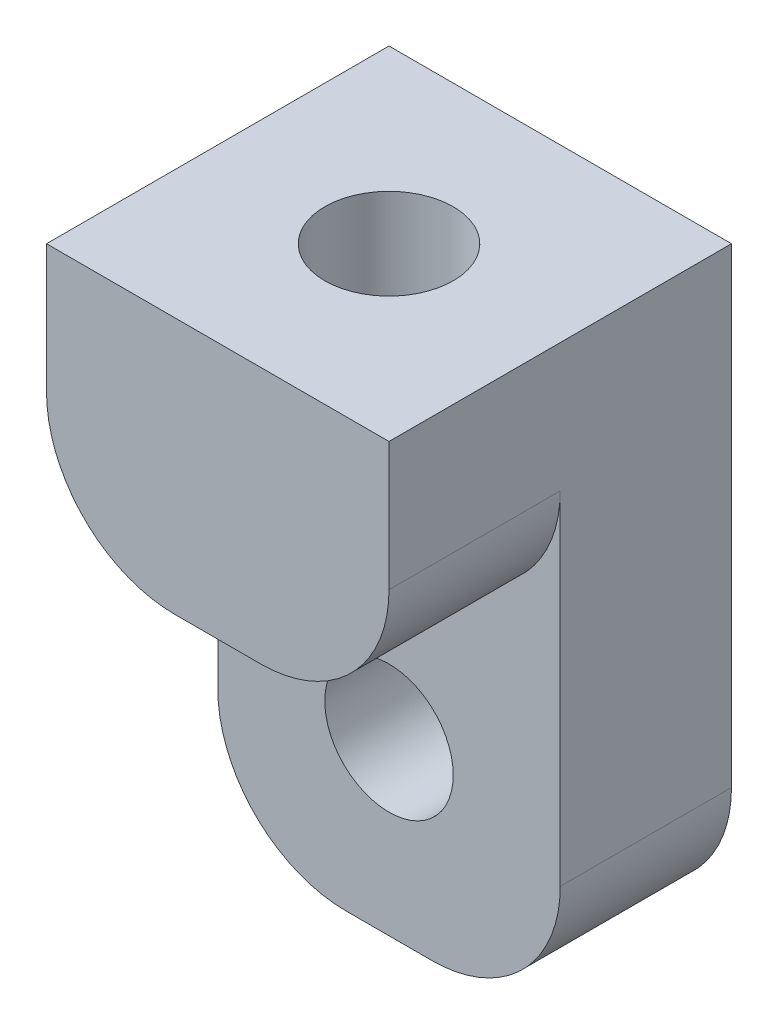
SolidWorks part; units mm, degrees
material "ABS"
ref_plane "Front Plane" through (0, 0, 0) normal (0, 0, 1) x (1, 0, 0)
ref_plane "Top Plane" through (0, 0, 0) normal (0, 1, 0) x (1, 0, 0)
ref_plane "Right Plane" through (0, 0, 0) normal (1, 0, 0) x (0, 0, -1)
sketch "Sketch1" plane through (0, 0, 0) normal (0, 0, 1) x (1, 0, 0)
  line L1 (-20, 50) -> (20, 50)
  line L2 (-20, 50) -> (-20, -20)
  line L3 (-20, -20) -> (20, -20)
  line L4 (20, 50) -> (20, -20)
  circle A0 centre (0, 0) radius 7.5
  point P9 (0, -20)
  dimension "D1" = 15
  dimension "D2" = 20
  dimension "D3" = 70
  dimension "D4" = 40
extrude "Boss-Extrude1" add sketch "Sketch1" along normal blind 40 contours L2 L3 L4 L1
sketch "Sketch2" plane through (0, 50, 0) normal (0, 1, 0) x (1, 0, 0)
  line L0 (-20, 0) -> (20, -40) construction
  line L4 (20, 0) -> (-20, 0)
  line L5 (-20, 0) -> (-20, -40)
  line L6 (-20, -40) -> (20, -40)
  line L7 (20, -40) -> (20, 0)
  line L8 (20, 0) -> (-20, 0)
  line L9 (-20, 0) -> (-20, -40)
  line L10 (-20, -40) -> (20, -40)
  line L11 (20, -40) -> (20, 0)
  circle A0 centre (0, -20) radius 7.5
  dimension "D2" = 15
  dimension "D1" = 0
extrude "Cut-Extrude1" cut sketch "Sketch2" against normal blind 20 contours L0 A0 | A0 L0
sketch "Sketch3" plane through (0, 0, 40) normal (0, 0, 1) x (1, 0, 0)
  line L0 (20, -20) -> (20, 50) construction
  line L1 (-20, -20) -> (20, -20)
  line L2 (-20, -20) -> (-20, 20)
  line L3 (-20, 20) -> (20, 20)
  line L4 (20, -20) -> (20, 20)
  dimension "D1" = 40
extrude "Cut-Extrude2" cut sketch "Sketch3" against normal blind 20 contours L2 L3 L4 L1
fillet "Fillet1" radius 15 4 edges at (-20, 20, 30) (20, 20, 30) (20, -20, 10) (-20, -20, 10)
